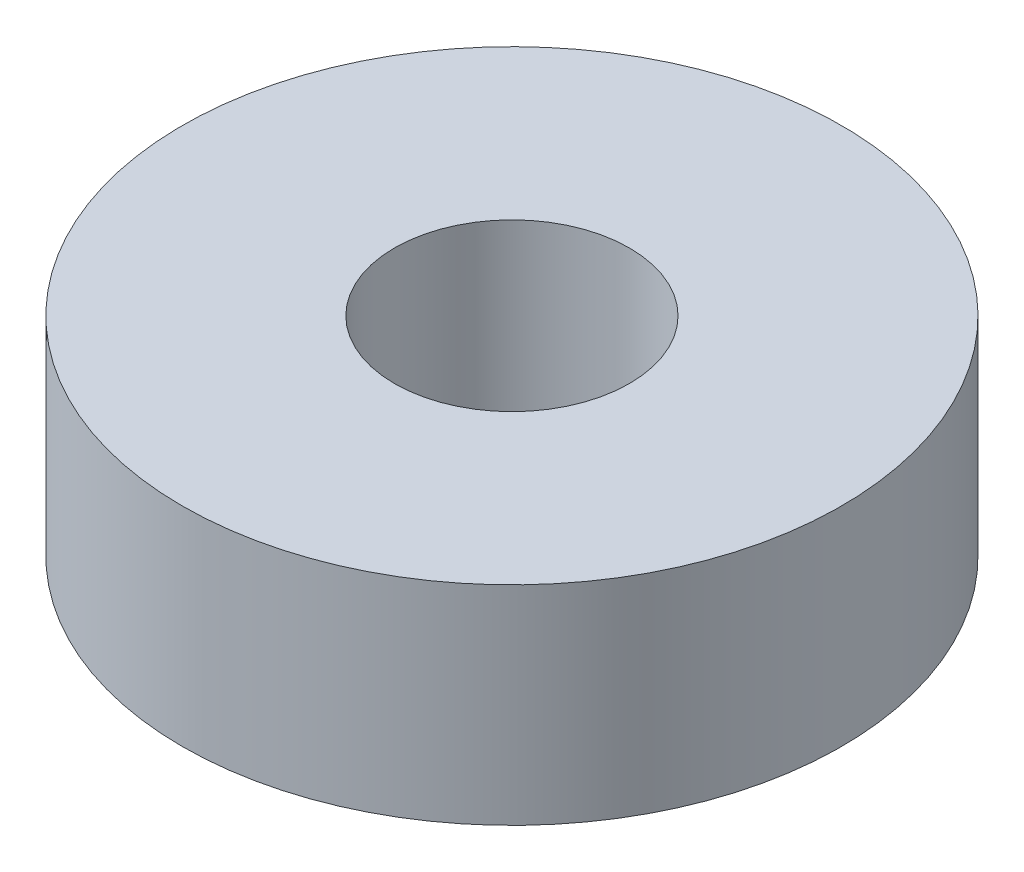
SolidWorks part; units mm, degrees
ref_plane "Front Plane" through (0, 0, 0) normal (0, 0, 1) x (1, 0, 0)
ref_plane "Top Plane" through (0, 0, 0) normal (0, 1, 0) x (1, 0, 0)
ref_plane "Right Plane" through (0, 0, 0) normal (1, 0, 0) x (0, 0, -1)
sketch "Sketch1" plane through (0, 0, 0) normal (0, 1, 0) x (1, 0, 0)
  circle A0 centre (0, 0) radius 3.925
  circle A1 centre (0, 0) radius 11.01
  dimension "D1" = 7.85
  dimension "D2" = 22.02
extrude "Boss-Extrude1" add sketch "Sketch1" along normal blind 6.96
